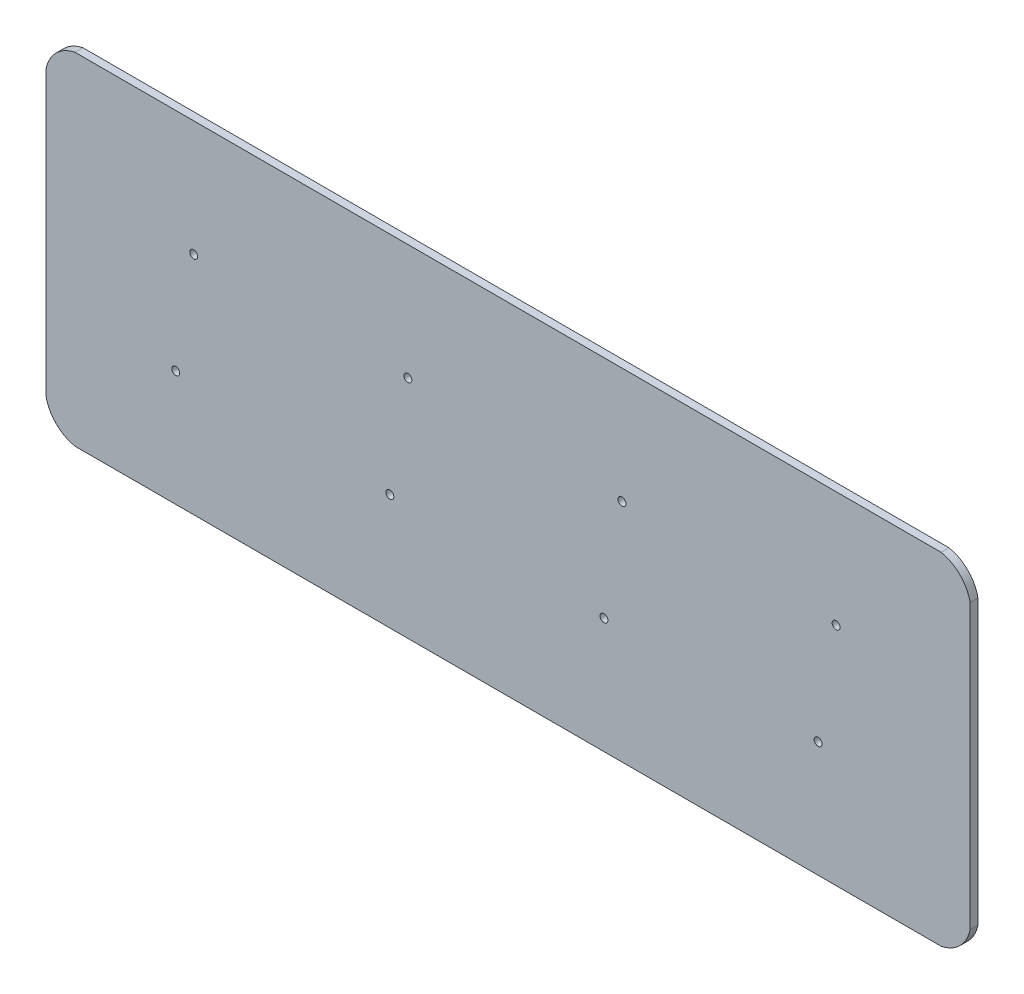
SolidWorks part; units mm, degrees
material "Maple"
ref_plane "Alzado" through (0, 0, 0) normal (0, 0, 1) x (1, 0, 0)
ref_plane "Planta" through (0, 0, 0) normal (0, 1, 0) x (1, 0, 0)
ref_plane "Vista lateral" through (0, 0, 0) normal (1, 0, 0) x (0, 0, -1)
sketch "Model" plane through (0, 0, 0) normal (0, 0, 1) x (1, 0, 0)
  line L311 (169.8255, 67.5031) -> (-160.1745, 67.5031)
  line L643 (180.8859, -51.4365) -> (180.8859, 56.4428)
  line L644 (-160.1745, -62.4969) -> (169.8255, -62.4969)
  line L645 (-171.2349, 56.4428) -> (-171.2349, -51.4365)
  circle A0 centre (-114.9449, 23.4531) radius 1.5
  circle A1 centre (-121.8049, -18.4569) radius 1.5
  circle A2 centre (-33.3549, 23.4531) radius 1.5
  circle A3 centre (-40.2149, -18.4569) radius 1.5
  circle A4 centre (48.2351, 23.4531) radius 1.5
  circle A5 centre (41.3751, -18.4569) radius 1.5
  circle A7 centre (129.8251, 23.4531) radius 1.5
  circle A8 centre (122.9651, -18.4569) radius 1.5
  arc A34 (180.8859, 56.4428) -> (169.8255, 67.5031) centre (167.1449, 53.7622) ccw
  arc A35 (-171.2349, -51.4365) -> (-160.1745, -62.4969) centre (-157.4939, -48.7559) ccw
  arc A36 (-160.1745, 67.5031) -> (-171.2349, 56.4428) centre (-157.4939, 53.7622) ccw
  arc A37 (169.8255, -62.4969) -> (180.8859, -51.4365) centre (167.1449, -48.7559) ccw
  dimension "D3" = 3
  dimension "D4" = 56.29
  dimension "D6" = 3
  dimension "D7" = 44.04
  dimension "D8" = 49.43
  dimension "D1" = 130
  dimension "D2" = 352.1207
  dimension "D5" = 44.05
  dimension "D9" = 4
extrude "Saliente-Extruir1" add sketch "Model" along normal blind 3
